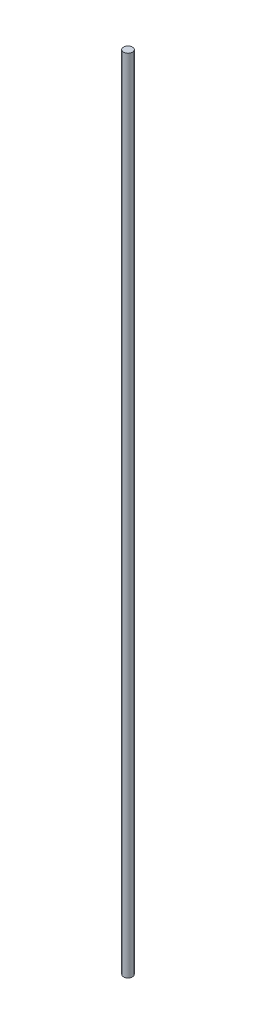
SolidWorks part; units mm, degrees
ref_plane "Front Plane" through (0, 0, 0) normal (0, 0, 1) x (1, 0, 0)
ref_plane "Top Plane" through (0, 0, 0) normal (0, 1, 0) x (1, 0, 0)
ref_plane "Right Plane" through (0, 0, 0) normal (1, 0, 0) x (0, 0, -1)
sketch "Sketch4" plane through (0, 0, 0) normal (0, 1, 0) x (1, 0, 0)
  circle A0 centre (0, 0) radius 5.08
  dimension "D1" = 10.16
extrude "Boss-Extrude1" add sketch "Sketch4" along normal blind 914.4
